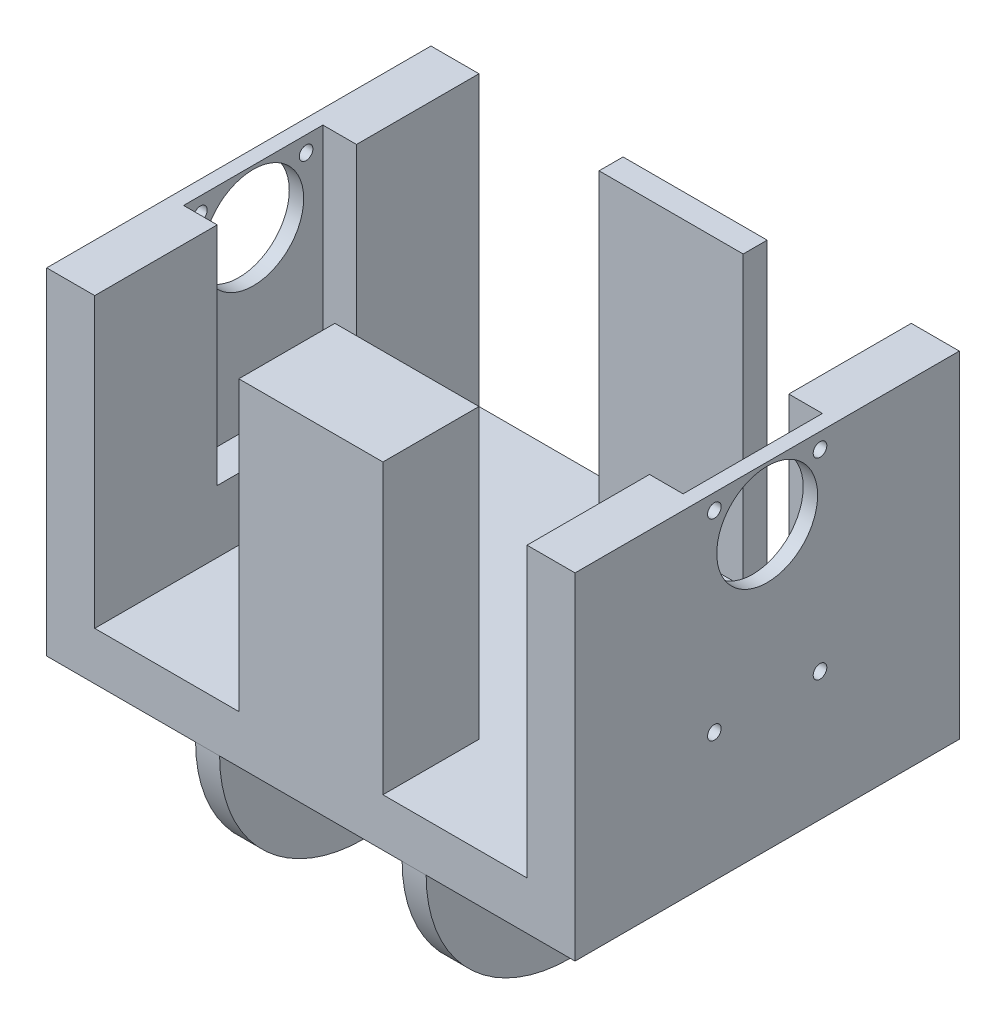
SolidWorks part; units mm, degrees
ref_plane "Front Plane" through (0, 0, 0) normal (0, 0, 1) x (1, 0, 0)
ref_plane "Top Plane" through (0, 0, 0) normal (0, 1, 0) x (1, 0, 0)
ref_plane "Right Plane" through (0, 0, 0) normal (1, 0, 0) x (0, 0, -1)
sketch "Sketch1" plane through (0, 0, 0) normal (0, 0, 1) x (1, 0, 0)
  line L1 (-55, 35) -> (55, 35)
  line L2 (-55, 35) -> (-55, -35)
  line L3 (-55, -35) -> (55, -35)
  line L4 (55, 35) -> (55, -35)
  line L5 (-55, 35) -> (55, -35) construction
  line L6 (-55, -35) -> (55, 35) construction
  line L7 (19, -35) -> (-19, -35)
  line L11 (19, -35) -> (55, -35)
  line L12 (19, -35) -> (19, -65)
  line L13 (19, -65) -> (55, -65)
  line L14 (55, -35) -> (55, -65)
  line L15 (-19, -35) -> (-55, -35)
  line L16 (-19, -35) -> (-19, -65)
  line L17 (-19, -65) -> (-55, -65)
  line L18 (-55, -35) -> (-55, -65)
  line L19 (-55, -35) -> (-24, -35)
  line L20 (-55, -35) -> (-55, -65)
  line L21 (-55, -65) -> (-24, -65)
  line L22 (-24, -35) -> (-24, -65)
  line L23 (55, -35) -> (24, -35)
  line L24 (55, -35) -> (55, -65)
  line L25 (55, -65) -> (24, -65)
  line L26 (24, -35) -> (24, -65)
  point P0 (0, 0)
  dimension "D1" = 110
  dimension "D2" = 70
  dimension "D3" = 36
  dimension "D4" = 36
  dimension "D5" = 30
  dimension "D6" = 30
  dimension "D7" = 5
  dimension "D8" = 5
extrude "Boss-Extrude1" add sketch "Sketch1" along normal blind 80 contours L4 L1 L2 L3 L15 L11 | L15 L22 L17 L16 | L26 L3 L12 L13
sketch "Sketch2" plane through (24, 0, 0) normal (1, 0, 0) x (0, 0, -1)
  line L0 (0, -35) -> (0, -65) construction
  line L1 (-80, -65) -> (0, -65) construction
  circle A0 centre (-40, -53) radius 10.25
  circle A1 centre (-40, -53) radius 8
  circle A2 centre (-40, -45) radius 1.2
  circle A3 centre (-40, -53) radius 8
  circle A4 centre (-32, -53) radius 1.2
  circle A5 centre (-40, -53) radius 8
  circle A6 centre (-40, -61) radius 1.2
  circle A7 centre (-40, -53) radius 8
  circle A8 centre (-48, -53) radius 1.2
  circle A9 centre (-40, -53) radius 4.4
  point P21 (-40, -53)
  dimension "D1" = 40
  dimension "D2" = 12
  dimension "D3" = 4
  dimension "D4" = 8.8
  dimension "D5" = 2.4
  dimension "D7" = 20
extrude "Cut-Extrude1" cut sketch "Sketch2" against normal blind 80 contours A7 A8 | A7 A8 | A1 A2 | A1 A2 | A3 A4 | A3 A4 | A5 A6 | A5 A6 | A9
sketch "Sketch4" plane through (0, 35, 0) normal (0, 1, 0) x (1, 0, 0)
  line L0 (-55, -80) -> (55, -80) construction
  line L1 (-45, -80) -> (-15, -80)
  line L2 (-45, -80) -> (-45, 0)
  line L3 (-45, 0) -> (-15, 0)
  line L4 (-15, -80) -> (-15, 0)
  line L5 (0, 0) -> (0, -32.8085) construction
  line L6 (-55, 0) -> (55, 0) construction
  line L7 (-55, -80) -> (-55, 0) construction
  line L8 (15, -80) -> (15, 0)
  line L9 (45, 0) -> (15, 0)
  line L10 (45, -80) -> (45, 0)
  line L11 (45, -80) -> (15, -80)
  line L13 (-15, 0) -> (15, 0)
  line L14 (-15, 0) -> (-15, -60)
  line L15 (-15, -60) -> (15, -60)
  line L16 (0, 0) -> (0, -60)
  line L17 (-15, 0) -> (15, 0)
  line L18 (-15, 0) -> (-15, -5)
  line L19 (-15, -5) -> (15, -5)
  line L20 (15, 0) -> (15, -5)
  line M6 (-55, -80) -> (55, -80)
  dimension "D1" = 30
  dimension "D2" = 0
  dimension "D3" = 10
  dimension "D4" = 20
  dimension "D5" = 5
extrude "Cut-Extrude3" cut sketch "Sketch4" against normal blind 60 contours L4 L3 L2 M6 | L10 L9 L8 M6 | L13 L16 L15 L8 | L16 L13 L4 L15
fillet "Fillet1" radius 30 4 edges at (-21.5, -65, 0) (-21.5, -65, 80) (21.5, -65, 0) (21.5, -65, 80)
sketch "Sketch6" plane through (55, 0, 0) normal (1, 0, 0) x (0, 0, -1)
  line L0 (-80, 35) -> (0, 35) construction
  line L1 (-54.25, 35) -> (-25.75, 35)
  line L2 (-54.25, 35) -> (-54.25, -11.5)
  line L3 (-54.25, -11.5) -> (-25.75, -11.5)
  line L4 (-25.75, 35) -> (-25.75, -11.5)
  line L5 (-80, 35) -> (-80, -35) construction
  circle A0 centre (-40, 23.75) radius 10.5
  circle A1 centre (-51, 31.75) radius 1.4145
  circle A2 centre (-29, 31.75) radius 1.4145
  circle A3 centre (-29, -8.25) radius 1.4145
  circle A4 centre (-51, -8.25) radius 1.4145
  dimension "D1" = 28.5
  dimension "D3" = 11.25
  dimension "D5" = 14.25
  dimension "D6" = 3.25
  dimension "D7" = 3.25
  dimension "D10" = 21
  dimension "D2" = 25.75
  dimension "D4" = 46.5
  dimension "D8" = 2
  dimension "D9" = 2
extrude "Cut-Extrude4" cut sketch "Sketch6" against normal through all contours A0 | A1 | A2 | A4 | A3
sketch "Sketch8" plane through (0, 35, 0) normal (0, 1, 0) x (1, 0, 0)
  line L0 (-55, -80) -> (-55, 0) construction
  line L1 (-55, -25.5) -> (-45, -25.5)
  line L2 (-55, -25.5) -> (-55, -54.5)
  line L3 (-55, -54.5) -> (-45, -54.5)
  line L4 (-45, -25.5) -> (-45, -54.5)
  line L5 (-45, -80) -> (-45, 0) construction
  line L6 (0, 0) -> (0, -26.5561) construction
  line L7 (-55, 0) -> (-45, 0) construction
  line L8 (45, -25.5) -> (45, -54.5)
  line L9 (55, -54.5) -> (45, -54.5)
  line L10 (55, -25.5) -> (55, -54.5)
  line L11 (55, -25.5) -> (45, -25.5)
  line L14 (52, -25.5) -> (52, -54.5)
  line L15 (-55, -25.5) -> (-52, -25.5)
  line L16 (-55, -25.5) -> (-55, -54.5)
  line L17 (-55, -54.5) -> (-52, -54.5)
  line L18 (-52, -25.5) -> (-52, -54.5)
  line L19 (55, -54.5) -> (52, -54.5)
  line L20 (55, -25.5) -> (55, -54.5)
  line L21 (55, -25.5) -> (52, -25.5)
  line L22 (45, -25.5) -> (45, -54.5)
  line L23 (55, -54.5) -> (45, -54.5)
  line L24 (55, -25.5) -> (55, -54.5)
  line L25 (55, -25.5) -> (45, -25.5)
  line M7 (-45, -80) -> (-45, 0)
  dimension "D1" = 29
  dimension "D2" = 25.5
  dimension "D3" = 3
extrude "Cut-Extrude5" cut sketch "Sketch8" against normal blind 47 contours L1 L18 L3 M7 | L14 L11 L8 L9
